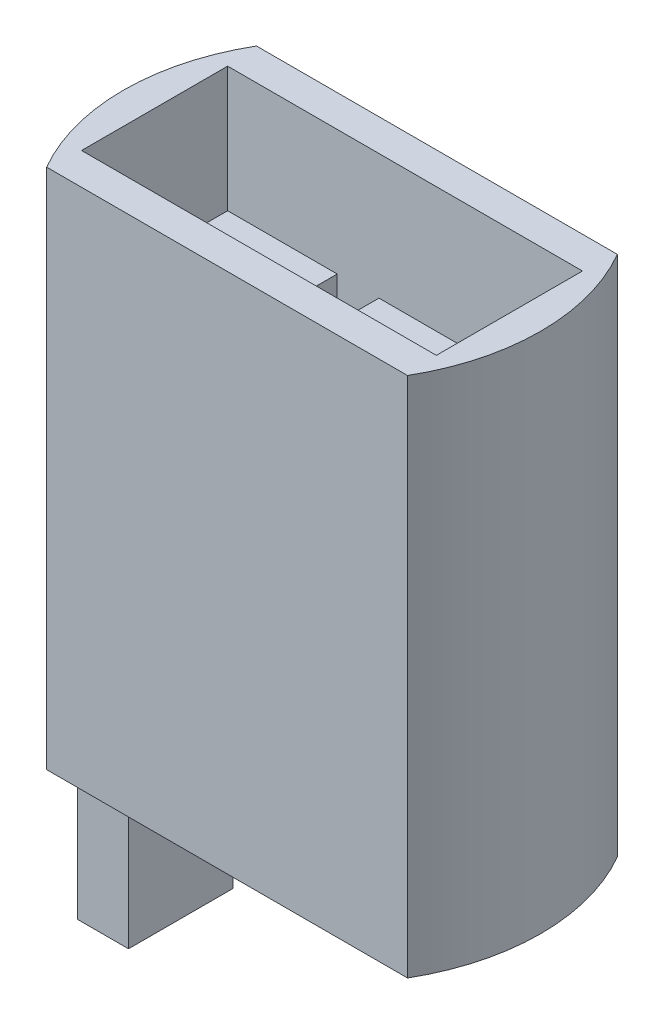
SolidWorks part; units mm, degrees
ref_plane "Front Plane" through (0, 0, 0) normal (0, 0, 1) x (1, 0, 0)
ref_plane "Top Plane" through (0, 0, 0) normal (0, 1, 0) x (1, 0, 0)
ref_plane "Right Plane" through (0, 0, 0) normal (1, 0, 0) x (0, 0, -1)
sketch "Sketch1" plane through (0, 0, 0) normal (0, 1, 0) x (1, 0, 0)
  circle A0 centre (0, 0) radius 10
  dimension "D1" = 20
extrude "Boss-Extrude1" add sketch "Sketch1" along normal blind 25
sketch "Sketch2" plane through (0, 0, 0) normal (0, -1, 0) x (-1, 0, 0)
  line L1 (8.05, 2.5) -> (7.25, 2.5)
  line L2 (8.05, 2.5) -> (8.05, -2.5)
  line L3 (8.05, -2.5) -> (7.25, -2.5)
  line L4 (7.25, 2.5) -> (7.25, -2.5)
  point P4 (7.25, 0)
  dimension "D1" = 5
  dimension "D2" = 0.8
  dimension "D3" = 7.25
extrude "Boss-Extrude2" add sketch "Sketch2" along normal blind 8 separate body
sketch "Sketch3" plane through (-8.05, 0, 0) normal (-1, 0, 0) x (0, 0, 1)
  line L0 (-2.5, -8) -> (-2.5, 0)
  line L1 (-2.5, 0) -> (2.5, 0)
  line L2 (2.5, 0) -> (2.5, -8)
  line L3 (2.5, -8) -> (1.5, -8)
  line L4 (2.5, -8) -> (-2.5, -8) construction
  line L5 (1.5, -8) -> (1.5, -0.75)
  line L6 (1.5, -0.75) -> (-1.5, -0.75)
  line L7 (-1.5, -0.75) -> (-1.5, -8)
  line L8 (-1.5, -8) -> (-2.5, -8)
  dimension "D1" = 1
  dimension "D2" = 1
  dimension "D3" = 0.75
extrude "Boss-Extrude3" add sketch "Sketch3" along normal blind 1.2
sketch "Sketch4" plane through (0, 25, 0) normal (0, 1, 0) x (1, 0, 0)
  line L0 (-10, 0) -> (10, 0) construction
  line L1 (-8.5, -3.5) -> (8.5, -3.5)
  line L2 (-8.5, -3.5) -> (-8.5, 3.5)
  line L3 (-8.5, 3.5) -> (8.5, 3.5)
  line L4 (8.5, -3.5) -> (8.5, 3.5)
  circle A0 centre (0, 0) radius 10 construction
  point P9 (-8.5, 0)
  dimension "D1" = 7
  dimension "D2" = 17
  dimension "D3" = 1.5
extrude "Cut-Extrude1" cut sketch "Sketch4" against normal blind 6
sketch "Sketch5" plane through (0, 19, 0) normal (0, 1, 0) x (1, 0, 0)
  line L0 (8.5, 0) -> (-1.25, 0) construction
  line L1 (8.5, -3.5) -> (8.5, 3.5) construction
  line L2 (8.5, 3.5) -> (-8.5, 3.5) construction
  line L3 (-1.25, 3.5) -> (-3.25, 3.5)
  line L4 (-1.25, 3.5) -> (-1.25, -3.5)
  line L5 (-1.25, -3.5) -> (-3.25, -3.5)
  line L6 (-3.25, 3.5) -> (-3.25, -3.5)
  line L7 (-8.5, -3.5) -> (8.5, -3.5) construction
  dimension "D1" = 9.75
  dimension "D2" = 2
extrude "Cut-Extrude2" cut sketch "Sketch5" against normal blind 4
sketch "Sketch6" plane through (0, 0, 0) normal (0, -1, 0) x (1, 0, 0)
  line L0 (-8.6446, 5.027) -> (8.6446, 5.027)
  line L1 (0, 0) -> (10, 0) construction
  line L2 (10, 0) -> (-10, 0) construction
  line L3 (-8.6446, -5.027) -> (8.6446, -5.027)
  arc A0 (-8.6446, 5.027) -> (8.6446, 5.027) centre (0, 0) cw
  circle A1 centre (0, 0) radius 10 construction
  circle A2 centre (0, 0) radius 10 construction
  arc A3 (-8.6446, -5.027) -> (8.6446, -5.027) centre (0, 0) ccw
  dimension "D1" = 8.6446
extrude "Cut-Extrude3" cut sketch "Sketch6" against normal blind 25
sketch "Sketch7" plane through (-9.25, 0, 0) normal (-1, 0, 0) x (0, 0, 1)
  line L1 (-2.5, -8) -> (2.5, -8)
  line L2 (-2.5, -8) -> (-2.5, 0)
  line L3 (-2.5, 0) -> (2.5, 0)
  line L4 (2.5, -8) -> (2.5, 0)
extrude "Boss-Extrude4" add sketch "Sketch7" along normal blind 0.8
sketch "Sketch8" plane through (0, 0, 0) normal (0, 1, 0) x (1, 0, 0)
  line L0 (-9.6825, 2.5) -> (-10.05, 2.5)
  line L1 (-10.05, 2.5) -> (-10.05, -2.5)
  line L2 (-10.05, -2.5) -> (-10.05, 2.5) construction
  line L3 (-10.05, -2.5) -> (-9.6825, -2.5)
  line L4 (-9.6825, -2.5) -> (-10.05, -2.5) construction
  arc A0 (-9.6825, 2.5) -> (-9.6825, -2.5) centre (0, 0) ccw construction
  arc A1 (-9.6825, 2.5) -> (-9.6825, -2.5) centre (0, 0) ccw
extrude "Cut-Extrude4" cut sketch "Sketch8" against normal up to next
